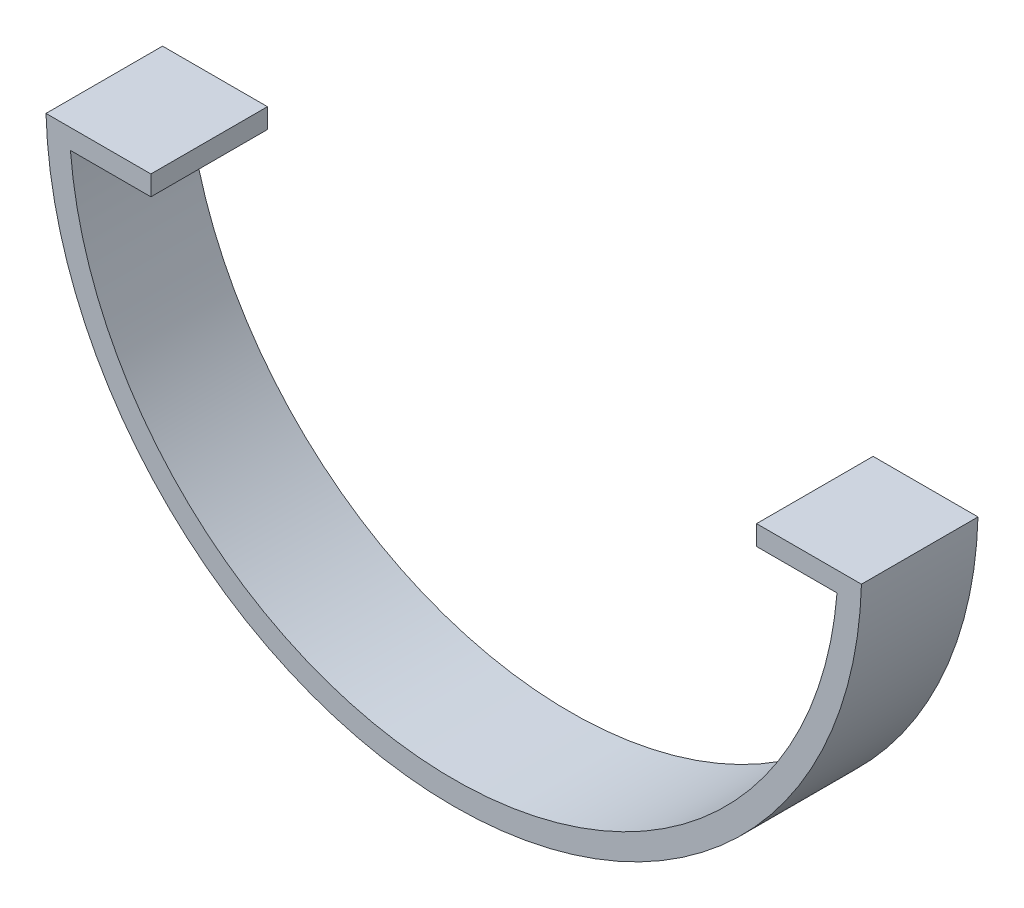
SolidWorks part; units mm, degrees
ref_plane "Front Plane" through (0, 0, 0) normal (0, 0, 1) x (1, 0, 0)
ref_plane "Top Plane" through (0, 0, 0) normal (0, 1, 0) x (1, 0, 0)
ref_plane "Right Plane" through (0, 0, 0) normal (1, 0, 0) x (0, 0, -1)
sketch "Sketch1" plane through (0, 0, 0) normal (0, 0, 1) x (1, 0, 0)
  line L0 (-34.9857, -1) -> (-32.9848, -1)
  line L1 (32.9848, -1) -> (34.9857, -1)
  line L2 (-32.9848, -1) -> (-25.9848, -1)
  line L3 (-25.9848, -1) -> (-25.9848, -2.7)
  line L4 (-25.9848, -2.7) -> (-32.8894, -2.7)
  line L5 (32.9848, -1) -> (25.9848, -1)
  line L6 (25.9848, -1) -> (25.9848, -2.7)
  line L7 (25.9848, -2.7) -> (32.8894, -2.7)
  arc A0 (-32.8894, -2.7) -> (32.8894, -2.7) centre (0, 0) ccw
  arc A1 (-34.9857, -1) -> (34.9857, -1) centre (0, 0) ccw
  arc A2 (34.9857, -1) -> (-34.9857, -1) centre (0, 0) ccw construction
  arc A3 (32.9848, -1) -> (-32.9848, -1) centre (0, 0) ccw construction
  arc A4 (32.8894, -2.7) -> (32.9848, -1) centre (0, 0) ccw construction
  arc A5 (-32.9848, -1) -> (-32.8894, -2.7) centre (0, 0) ccw construction
  point P1 (0, 0)
  point P13 (-33, -1.6585)
  dimension "D1" = 33
  dimension "D2" = 35
  dimension "D3" = 1.7
  dimension "D4" = 1
  dimension "D5" = 7
extrude "Boss-Extrude1" add sketch "Sketch1" along normal blind 10
